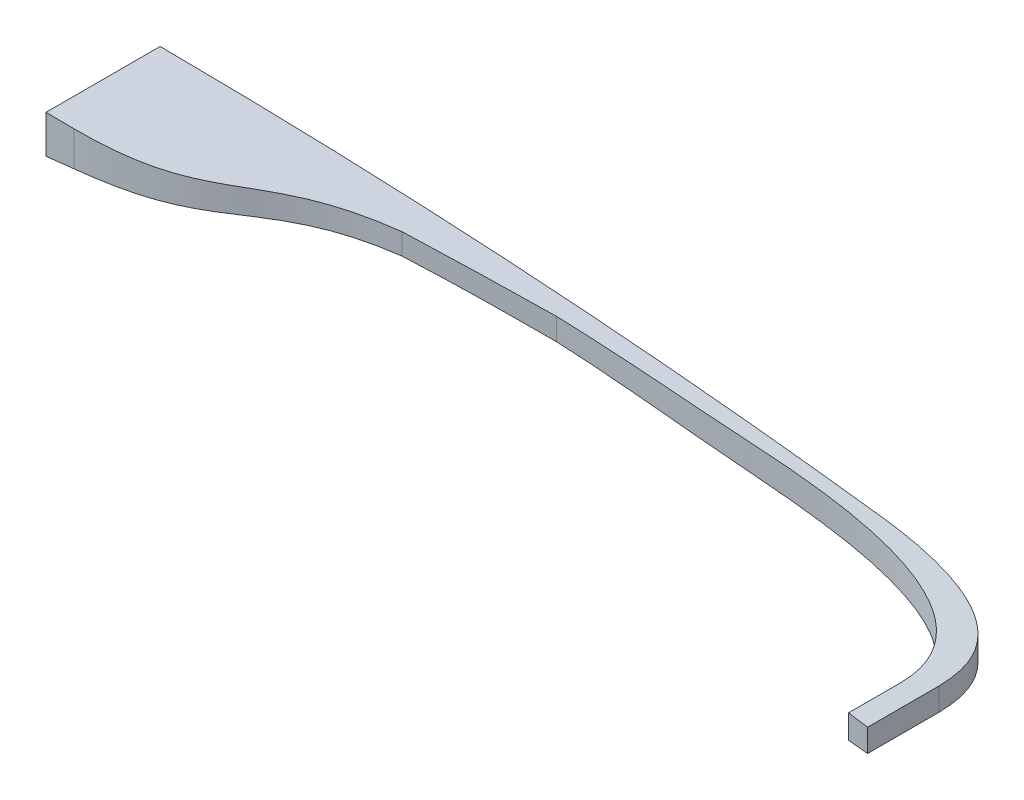
SolidWorks part; units mm, degrees
ref_plane "Front Plane" through (0, 0, 0) normal (0, 0, 1) x (1, 0, 0)
ref_plane "Top Plane" through (0, 0, 0) normal (0, 1, 0) x (1, 0, 0)
ref_plane "Right Plane" through (0, 0, 0) normal (1, 0, 0) x (0, 0, -1)
sketch "Sketch1" plane through (0, 0, 0) normal (0, 1, 0) x (1, 0, 0)
  line L1 (0, 0) -> (146.05, 0)
  line L2 (0, 0) -> (0, 19.05)
  line L3 (0, 19.05) -> (146.05, 19.05)
  line L4 (146.05, 0) -> (146.05, 19.05)
  dimension "D1" = 146.05
  dimension "D2" = 19.05
extrude "Boss-Extrude1" add sketch "Sketch1" along normal blind 15.24
sketch "Sketch3" plane through (0, 0, -19.05) normal (0, 0, -1) x (-1, 0, 0)
  line L0 (0, 15.24) -> (0, 0) construction
  line L1 (-146.05, 15.24) -> (-146.05, 0) construction
  spline S0 degree 3 poles (0, 8.89) (-49.1571, 14.8351) (-97.485, 4.9116) (-146.05, 0) knots 0 0 0 0 1 1 1 1
  spline S1 degree 3 poles (0, 15.24) (-48.867, 14.9447) (-97.7661, 11.394) (-146.05, 3.81) knots 0 0 0 0 1 1 1 1
  line M1 (-146.05, 0) -> (0, 0)
  line M2 (0, 0) -> (0, 15.24)
  line M3 (0, 15.24) -> (-146.05, 15.24)
  line M4 (-146.05, 15.24) -> (-146.05, 0)
  dimension "D1" = 6.35
  dimension "D2" = 3.81
  dimension "D3" = 4.445
  dimension "D4" = 3.6908
sketch "Sketch4" plane through (0, 15.24, 0) normal (0, 1, 0) x (1, 0, 0)
  line L3 (4.6463, 0) -> (142.875, 0)
  line L4 (146.05, 0) -> (146.05, 19.05)
  line L5 (146.05, 19.05) -> (120.8556, 19.05)
  line L6 (0, 0) -> (146.05, 0) construction
  line L7 (146.05, 0) -> (146.05, 19.05) construction
  spline S0 degree 3 poles (4.6463, 0) (27.1465, 0.0824) (23.2094, 15.8542) (86.1202, 16.1335) (108.0442, 16.6822) (142.5976, 19.0111) (142.875, 0) knots 0 0 0 0 0.354963 0.569522 0.634026 1 1 1 1
  spline S1 degree 3 poles (120.8556, 19.05) (147.3947, 18.9666) (146.048, 6.8243) (146.05, 0) knots 0 0 0 0 1 1 1 1
  spline S2 degree 1 poles (45.7201, 13.7131) (69.3914, 15.8142) knots 0 0 1 1
  point P6 (57.8485, 9.8715)
  point P13 (17.5743, 0)
  point P14 (4.7388, 0)
  point P15 (45.0503, 14.7424)
  point P17 (93.9529, 15.1639)
  point P18 (70.1175, 16.7898)
  point P19 (45.7939, 15.618)
  point P20 (93.4866, 17.611)
  point P21 (0, 0)
  point P22 (45.7472, 15.6923)
  point P23 (69.3919, 15.8016)
  point P24 (0, 0)
  point P26 (0, 0)
  point P27 (0, 0)
  line M2 (146.05, 19.05) -> (0, 19.05)
  line M4 (0, 0) -> (146.05, 0)
  dimension "D1" = 3.175
extrude "Cut-Extrude2" cut sketch "Sketch4" against normal blind 19.05 contours S2 S0 M4 | S1 L4 M2
extrude "Cut-Extrude3" cut sketch "Sketch3" against normal through all contours S0 M2 M1 | S1 M3 M4
sketch "Sketch5" plane through (0, 0, 0) normal (-1, 0, 0) x (0, 0, 1)
  line L0 (0, 8.89) -> (-19.05, 8.89) construction
  line L1 (-6.35, 8.89) -> (-12.7, 8.89)
  line L2 (-6.35, 8.89) -> (-6.35, 12.7)
  line L3 (-6.35, 12.7) -> (-12.7, 12.7)
  line L4 (-12.7, 8.89) -> (-12.7, 12.7)
  line L5 (-19.05, 15.24) -> (-19.05, 8.89) construction
  dimension "D1" = 3.81
  dimension "D2" = 6.35
  dimension "D3" = 6.35
extrude "Cut-Extrude4" cut sketch "Sketch5" against normal blind 5.08
sketch "Sketch7" plane through (0, 0, 0) normal (0, 0, 1) x (1, 0, 0)
  line L0 (144.1614, 1.9051) -> (146.05, 3.81)
extrude "Boss-Extrude2" add sketch "Sketch7" along normal blind 8.89
